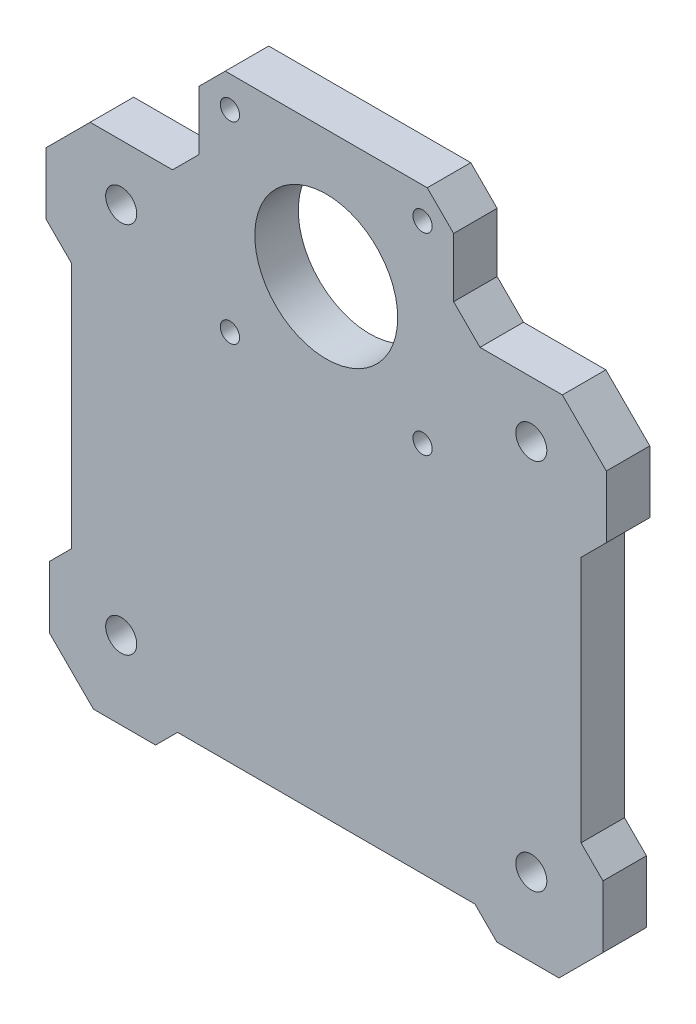
SolidWorks part; units mm, degrees
ref_plane "Alzado" through (0, 0, 0) normal (0, 0, 1) x (1, 0, 0)
ref_plane "Planta" through (0, 0, 0) normal (0, 1, 0) x (1, 0, 0)
ref_plane "Vista lateral" through (0, 0, 0) normal (1, 0, 0) x (0, 0, -1)
sketch "Croquis1" plane through (0, 0, 0) normal (0, 0, 1) x (1, 0, 0)
  line L0 (0, 0) -> (0, 36.5) construction
  line L5 (33, 30) -> (-33, 30)
  line L10 (33, 30) -> (33, -30)
  line L11 (33, -30) -> (-33, -30)
  line L12 (-33, 30) -> (-33, -30)
  line L13 (33, 30) -> (-33, -30) construction
  line L14 (33, -30) -> (-33, 30) construction
  line L15 (-41, 39) -> (41, 39)
  line L16 (-41, 39) -> (-41, -39)
  line L17 (-41, -39) -> (41, -39)
  line L18 (41, 39) -> (41, -39)
  line L19 (-41, 39) -> (41, -39) construction
  line L20 (-41, -39) -> (41, 39) construction
  line L22 (-20.5, 16) -> (20.5, 16)
  line L23 (-20.5, 16) -> (-20.5, 57)
  line L24 (-20.5, 57) -> (20.5, 57)
  line L25 (20.5, 16) -> (20.5, 57)
  line L26 (-20.5, 16) -> (20.5, 57) construction
  line L27 (-20.5, 57) -> (20.5, 16) construction
  circle A0 centre (-33, 30) radius 2.5
  circle A1 centre (33, 30) radius 2.5
  circle A2 centre (33, -30) radius 2.5
  circle A3 centre (-33, -30) radius 2.5
  circle A4 centre (0, 36.5) radius 11.5
  point P0 (0, 0)
  point P5 (0, 0)
  dimension "D5" = 36.5
  dimension "D6" = 23
  dimension "D1" = 66
  dimension "D2" = 60
  dimension "D3" = 78
  dimension "D4" = 82
  dimension "D7" = 41
  dimension "D8" = 41
extrude "Saliente-Extruir5" add sketch "Croquis1" along normal blind 7 contours A3 L11 A2 L10 A1 L5 L25 L22 L23 A0 L12 | A4 L5 L23 L22 L25 | A3 L12 A0 L5 L23 L15 L16 L17 L18 L25 A1 L10 A2 L11 | A4 L15 L25 L24 L23 | A4 L15 L23 L5 | A4 L5 L25 L15
sketch "Croquis5" plane through (0, 0, 7) normal (0, 0, 1) x (1, 0, 0)
  line L5 (15.5, 21) -> (-15.5, 21)
  line L6 (15.5, 21) -> (15.5, 52)
  line L7 (15.5, 52) -> (-15.5, 52)
  line L8 (-15.5, 21) -> (-15.5, 52)
  line L9 (15.5, 21) -> (-15.5, 52) construction
  line L10 (15.5, 52) -> (-15.5, 21) construction
  circle A0 centre (-15.5, 52) radius 1.55
  circle A1 centre (15.5, 52) radius 1.55
  circle A2 centre (15.5, 21) radius 1.55
  circle A3 centre (-15.5, 21) radius 1.55
  point P0 (0, 36.5)
  point P16 (0, 36.5)
  dimension "D2" = 3.1
  dimension "D1" = 31
  dimension "D3" = 4
extrude "Cortar-Extruir1" cut sketch "Croquis5" against normal through all contours A2 | A1 | A0 | A3
sketch "Croquis6" plane through (0, 0, 7) normal (0, 0, 1) x (1, 0, 0)
  line L0 (0, 0) -> (0, 57) construction
  line L1 (-20.5, 57) -> (20.5, 57) construction
  line L2 (-41, 39) -> (0, 39) construction
  line L3 (-38, 39) -> (38, 39)
  line L4 (20.5, 39) -> (41, 39) construction
  line L5 (38, 39) -> (45.0711, 31.9289)
  line L6 (38, 39) -> (38, -39) construction
  line L7 (-41, -39) -> (41, -39) construction
  line L8 (45.0711, 31.9289) -> (45.0711, 21.9289)
  line L9 (45.0711, 21.9289) -> (41, 17.8579)
  line L10 (41, -39) -> (44.5355, -35.4645)
  line L11 (41, 39) -> (41, -39) construction
  line L12 (44.5355, -35.4645) -> (44.5355, -25.4645)
  line L13 (45.0711, 21.9289) -> (41, 21.9289) construction
  line L14 (20.5, 43.2426) -> (24.7426, 39)
  line L15 (20.5, 39) -> (20.5, 57) construction
  line L16 (44.5355, -25.4645) -> (41, -21.9289)
  line L17 (44.5355, -35.4645) -> (37.4645, -42.5355)
  line L18 (37.4645, -42.5355) -> (27.4645, -42.5355)
  line L19 (27.4645, -42.5355) -> (23.9289, -39)
  line L20 (-45.0711, 21.9289) -> (-41, 21.9289) construction
  line L21 (-38, 39) -> (-38, -39) construction
  line L22 (-27.4645, -42.5355) -> (-23.9289, -39)
  line L23 (-37.4645, -42.5355) -> (-27.4645, -42.5355)
  line L24 (-44.5355, -35.4645) -> (-37.4645, -42.5355)
  line L25 (-44.5355, -25.4645) -> (-41, -21.9289)
  line L26 (-20.5, 43.2426) -> (-24.7426, 39)
  line L27 (-44.5355, -35.4645) -> (-44.5355, -25.4645)
  line L28 (-41, -39) -> (-44.5355, -35.4645)
  line L29 (-45.0711, 21.9289) -> (-41, 17.8579)
  line L30 (-45.0711, 31.9289) -> (-45.0711, 21.9289)
  line L31 (-38, 39) -> (-45.0711, 31.9289)
  line M21 (-20.5, 57) -> (-20.5, 39)
  line M22 (-20.5, 39) -> (-41, 39)
  line M23 (-41, 39) -> (-41, -39)
  line M24 (-41, -39) -> (41, -39)
  line M25 (41, -39) -> (41, 39)
  line M27 (20.5, 39) -> (20.5, 57)
  dimension "D1" = 17.5
  dimension "D2" = 10
  dimension "D3" = 10
  dimension "D4" = 45
  dimension "D5" = 45
  dimension "D6" = 45
  dimension "D7" = 6
  dimension "D8" = 45
  dimension "D9" = 45
  dimension "D10" = 10
  dimension "D11" = 45
extrude "Saliente-Extruir7" add sketch "Croquis6" against normal through all contours L31 L30 L29 M23 | L26 M21 M22 | L14 L3 M27 | L9 L8 L5 M25 | L12 L16 L10 M25 | L19 L18 L17 M24 | L27 L24 L25 M23 | L24 L23 L22 M24
sketch "Croquis7" plane through (0, 0, 7) normal (0, 0, 1) x (1, 0, 0)
  line L0 (-45.0711, 31.9289) -> (-38, 39)
  line L1 (-41, 39) -> (-24.7426, 39) construction
  line L2 (-38, 39) -> (-41, 39)
  line L3 (-41, 39) -> (-41, 36)
  line L4 (45.0711, 31.9289) -> (38, 39)
  line L5 (24.7426, 39) -> (41, 39) construction
  line L6 (38, 39) -> (41, 39)
  line L7 (41, 39) -> (41, 36)
  line L9 (16.2574, 57) -> (20.5, 52.7574)
  line L10 (-20.5, 57) -> (20.5, 57) construction
  line L11 (20.5, 43.2426) -> (20.5, 57) construction
  line L12 (0, 57) -> (0, 40.777) construction
  line L13 (-16.2574, 57) -> (-20.5, 52.7574)
  line L14 (-16.2574, 57) -> (-20.5, 57)
  line L15 (-20.5, 57) -> (-20.5, 52.7574)
  line L16 (16.2574, 57) -> (20.5, 57)
  line L17 (20.5, 57) -> (20.5, 52.7574)
  line M2 (41, 39) -> (24.7426, 39)
  line M4 (20.5, 43.2426) -> (20.5, 57)
  line M5 (20.5, 57) -> (-20.5, 57)
  line M6 (-20.5, 57) -> (-20.5, 43.2426)
  line M8 (-24.7426, 39) -> (-41, 39)
  line M9 (-41, 39) -> (-41, 36)
  line M29 (41, 36) -> (41, 39)
  dimension "D1" = 6
  dimension "D2" = 45
extrude "Cortar-Extruir2" cut sketch "Croquis7" against normal through all contours L13 M5 M6 | L9 M5 M4 | L0 M9 M8 | L4 M29 M2
